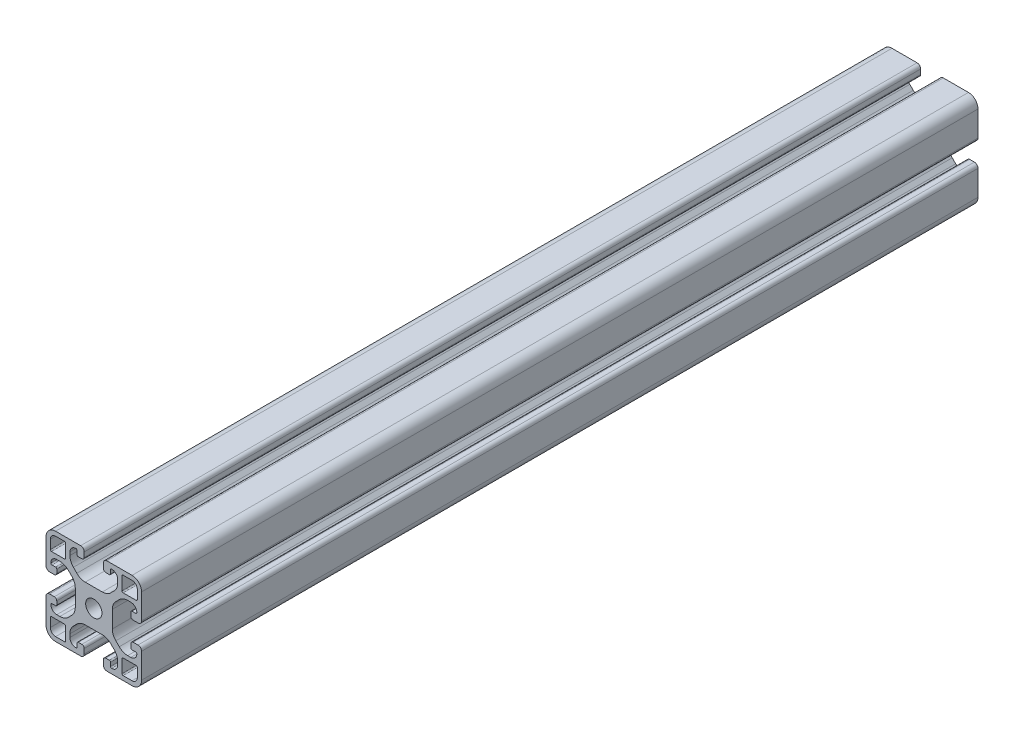
SolidWorks part; units mm, degrees
ref_plane "Front Plane" through (0, 0, 0) normal (0, 0, 1) x (1, 0, 0)
ref_plane "Top Plane" through (0, 0, 0) normal (0, 1, 0) x (1, 0, 0)
ref_plane "Right Plane" through (0, 0, 0) normal (1, 0, 0) x (0, 0, -1)
sketch "Sketch1" plane through (0, 0, 0) normal (0, 0, 1) x (1, 0, 0)
  line L0 (1.8, 4) -> (1.8, 7.7)
  line L1 (2.3, 8.2) -> (7.7, 8.2)
  line L2 (8.2, 7.7) -> (8.2, 2.3)
  line L3 (7.7, 1.8) -> (4, 1.8)
  line L4 (4, 38.2) -> (7.7, 38.2)
  line L5 (8.2, 37.7) -> (8.2, 32.3)
  line L6 (7.7, 31.8) -> (2.3, 31.8)
  line L7 (1.8, 32.3) -> (1.8, 36)
  line L8 (31.8, 32.3) -> (31.8, 37.7)
  line L9 (32.3, 38.2) -> (36, 38.2)
  line L10 (38.2, 36) -> (38.2, 32.3)
  line L11 (37.7, 31.8) -> (32.3, 31.8)
  line L12 (32.3, 8.2) -> (37.7, 8.2)
  line L13 (38.2, 7.7) -> (38.2, 4)
  line L14 (36, 1.8) -> (32.3, 1.8)
  line L15 (31.8, 2.3) -> (31.8, 7.7)
  line L16 (0, 36) -> (0, 25.5)
  line L17 (1.5, 24) -> (3.5, 24)
  line L18 (4.5, 25) -> (4.5, 26.5)
  line L19 (4, 27) -> (2.5, 27)
  line L20 (4.5, 30) -> (5.8076, 30)
  line L21 (9.3431, 28.5355) -> (10.7855, 27.0931)
  line L22 (12.25, 23.5576) -> (12.25, 16.4424)
  line L23 (10.7855, 12.9069) -> (9.3431, 11.4645)
  line L24 (5.8076, 10) -> (4.5, 10)
  line L25 (2.5, 13) -> (4, 13)
  line L26 (4.5, 13.5) -> (4.5, 15)
  line L27 (3.5, 16) -> (1.5, 16)
  line L28 (0, 14.5) -> (0, 4)
  line L29 (4, 0) -> (14.5, 0)
  line L30 (16, 1.5) -> (16, 3.5)
  line L31 (15, 4.5) -> (13.5, 4.5)
  line L32 (13, 4) -> (13, 2.5)
  line L33 (10, 4.5) -> (10, 5.8076)
  line L34 (11.4645, 9.3431) -> (12.9069, 10.7855)
  line L35 (16.4424, 12.25) -> (23.5576, 12.25)
  line L36 (27.0931, 10.7855) -> (28.5355, 9.3431)
  line L37 (30, 5.8076) -> (30, 4.5)
  line L38 (27, 2.5) -> (27, 4)
  line L39 (26.5, 4.5) -> (25, 4.5)
  line L40 (24, 3.5) -> (24, 1.5)
  line L41 (25.5, 0) -> (36, 0)
  line L42 (40, 4) -> (40, 14.5)
  line L43 (38.5, 16) -> (36.5, 16)
  line L44 (35.5, 15) -> (35.5, 13.5)
  line L45 (36, 13) -> (37.5, 13)
  line L46 (35.5, 10) -> (34.1924, 10)
  line L47 (30.6569, 11.4645) -> (29.2145, 12.9069)
  line L48 (27.75, 16.4424) -> (27.75, 23.5576)
  line L49 (29.2145, 27.0931) -> (30.6569, 28.5355)
  line L50 (34.1924, 30) -> (35.5, 30)
  line L51 (37.5, 27) -> (36, 27)
  line L52 (35.5, 26.5) -> (35.5, 25)
  line L53 (36.5, 24) -> (38.5, 24)
  line L54 (40, 25.5) -> (40, 36)
  line L55 (36, 40) -> (25.5, 40)
  line L56 (24, 38.5) -> (24, 36.5)
  line L57 (25, 35.5) -> (26.5, 35.5)
  line L58 (27, 36) -> (27, 37.5)
  line L59 (30, 35.5) -> (30, 34.1924)
  line L60 (28.5355, 30.6569) -> (27.0931, 29.2145)
  line L61 (23.5576, 27.75) -> (16.4424, 27.75)
  line L62 (12.9069, 29.2145) -> (11.4645, 30.6569)
  line L63 (10, 34.1924) -> (10, 35.5)
  line L64 (13, 37.5) -> (13, 36)
  line L65 (13.5, 35.5) -> (15, 35.5)
  line L66 (16, 36.5) -> (16, 38.5)
  line L67 (14.5, 40) -> (4, 40)
  arc A0 (1.8, 7.7) -> (2.3, 8.2) centre (2.3, 7.7) cw
  arc A1 (7.7, 8.2) -> (8.2, 7.7) centre (7.7, 7.7) cw
  arc A2 (8.2, 2.3) -> (7.7, 1.8) centre (7.7, 2.3) cw
  arc A3 (4, 1.8) -> (1.8, 4) centre (4, 4) cw
  arc A4 (1.8, 36) -> (4, 38.2) centre (4, 36) cw
  arc A5 (7.7, 38.2) -> (8.2, 37.7) centre (7.7, 37.7) cw
  arc A6 (8.2, 32.3) -> (7.7, 31.8) centre (7.7, 32.3) cw
  arc A7 (2.3, 31.8) -> (1.8, 32.3) centre (2.3, 32.3) cw
  circle A8 centre (20, 20) radius 3.4
  arc A9 (31.8, 37.7) -> (32.3, 38.2) centre (32.3, 37.7) cw
  arc A10 (36, 38.2) -> (38.2, 36) centre (36, 36) cw
  arc A11 (38.2, 32.3) -> (37.7, 31.8) centre (37.7, 32.3) cw
  arc A12 (32.3, 31.8) -> (31.8, 32.3) centre (32.3, 32.3) cw
  arc A13 (31.8, 7.7) -> (32.3, 8.2) centre (32.3, 7.7) cw
  arc A14 (37.7, 8.2) -> (38.2, 7.7) centre (37.7, 7.7) cw
  arc A15 (38.2, 4) -> (36, 1.8) centre (36, 4) cw
  arc A16 (32.3, 1.8) -> (31.8, 2.3) centre (32.3, 2.3) cw
  arc A17 (0, 25.5) -> (1.5, 24) centre (1.5, 25.5) ccw
  arc A18 (3.5, 24) -> (4.5, 25) centre (3.5, 25) ccw
  arc A19 (4.5, 26.5) -> (4, 27) centre (4, 26.5) ccw
  arc A20 (2.5, 27) -> (2, 27.5) centre (2.5, 27.5) cw
  arc A21 (2, 27.5) -> (4.5, 30) centre (4.5, 27.5) cw
  arc A22 (5.8076, 30) -> (9.3431, 28.5355) centre (5.8076, 25) cw
  arc A23 (10.7855, 27.0931) -> (12.25, 23.5576) centre (7.25, 23.5576) cw
  arc A24 (12.25, 16.4424) -> (10.7855, 12.9069) centre (7.25, 16.4424) cw
  arc A25 (9.3431, 11.4645) -> (5.8076, 10) centre (5.8076, 15) cw
  arc A26 (4.5, 10) -> (2, 12.5) centre (4.5, 12.5) cw
  arc A27 (2, 12.5) -> (2.5, 13) centre (2.5, 12.5) cw
  arc A28 (4, 13) -> (4.5, 13.5) centre (4, 13.5) ccw
  arc A29 (4.5, 15) -> (3.5, 16) centre (3.5, 15) ccw
  arc A30 (1.5, 16) -> (0, 14.5) centre (1.5, 14.5) ccw
  arc A31 (0, 4) -> (4, 0) centre (4, 4) ccw
  arc A32 (14.5, 0) -> (16, 1.5) centre (14.5, 1.5) ccw
  arc A33 (16, 3.5) -> (15, 4.5) centre (15, 3.5) ccw
  arc A34 (13.5, 4.5) -> (13, 4) centre (13.5, 4) ccw
  arc A35 (13, 2.5) -> (12.5, 2) centre (12.5, 2.5) cw
  arc A36 (12.5, 2) -> (10, 4.5) centre (12.5, 4.5) cw
  arc A37 (10, 5.8076) -> (11.4645, 9.3431) centre (15, 5.8076) cw
  arc A38 (12.9069, 10.7855) -> (16.4424, 12.25) centre (16.4424, 7.25) cw
  arc A39 (23.5576, 12.25) -> (27.0931, 10.7855) centre (23.5576, 7.25) cw
  arc A40 (28.5355, 9.3431) -> (30, 5.8076) centre (25, 5.8076) cw
  arc A41 (30, 4.5) -> (27.5, 2) centre (27.5, 4.5) cw
  arc A42 (27.5, 2) -> (27, 2.5) centre (27.5, 2.5) cw
  arc A43 (27, 4) -> (26.5, 4.5) centre (26.5, 4) ccw
  arc A44 (25, 4.5) -> (24, 3.5) centre (25, 3.5) ccw
  arc A45 (24, 1.5) -> (25.5, 0) centre (25.5, 1.5) ccw
  arc A46 (36, 0) -> (40, 4) centre (36, 4) ccw
  arc A47 (40, 14.5) -> (38.5, 16) centre (38.5, 14.5) ccw
  arc A48 (36.5, 16) -> (35.5, 15) centre (36.5, 15) ccw
  arc A49 (35.5, 13.5) -> (36, 13) centre (36, 13.5) ccw
  arc A50 (37.5, 13) -> (38, 12.5) centre (37.5, 12.5) cw
  arc A51 (38, 12.5) -> (35.5, 10) centre (35.5, 12.5) cw
  arc A52 (34.1924, 10) -> (30.6569, 11.4645) centre (34.1924, 15) cw
  arc A53 (29.2145, 12.9069) -> (27.75, 16.4424) centre (32.75, 16.4424) cw
  arc A54 (27.75, 23.5576) -> (29.2145, 27.0931) centre (32.75, 23.5576) cw
  arc A55 (30.6569, 28.5355) -> (34.1924, 30) centre (34.1924, 25) cw
  arc A56 (35.5, 30) -> (38, 27.5) centre (35.5, 27.5) cw
  arc A57 (38, 27.5) -> (37.5, 27) centre (37.5, 27.5) cw
  arc A58 (36, 27) -> (35.5, 26.5) centre (36, 26.5) ccw
  arc A59 (35.5, 25) -> (36.5, 24) centre (36.5, 25) ccw
  arc A60 (38.5, 24) -> (40, 25.5) centre (38.5, 25.5) ccw
  arc A61 (40, 36) -> (36, 40) centre (36, 36) ccw
  arc A62 (25.5, 40) -> (24, 38.5) centre (25.5, 38.5) ccw
  arc A63 (24, 36.5) -> (25, 35.5) centre (25, 36.5) ccw
  arc A64 (26.5, 35.5) -> (27, 36) centre (26.5, 36) ccw
  arc A65 (27, 37.5) -> (27.5, 38) centre (27.5, 37.5) cw
  arc A66 (27.5, 38) -> (30, 35.5) centre (27.5, 35.5) cw
  arc A67 (30, 34.1924) -> (28.5355, 30.6569) centre (25, 34.1924) cw
  arc A68 (27.0931, 29.2145) -> (23.5576, 27.75) centre (23.5576, 32.75) cw
  arc A69 (16.4424, 27.75) -> (12.9069, 29.2145) centre (16.4424, 32.75) cw
  arc A70 (11.4645, 30.6569) -> (10, 34.1924) centre (15, 34.1924) cw
  arc A71 (10, 35.5) -> (12.5, 38) centre (12.5, 35.5) cw
  arc A72 (12.5, 38) -> (13, 37.5) centre (12.5, 37.5) cw
  arc A73 (13, 36) -> (13.5, 35.5) centre (13.5, 36) ccw
  arc A74 (15, 35.5) -> (16, 36.5) centre (15, 36.5) ccw
  arc A75 (16, 38.5) -> (14.5, 40) centre (14.5, 38.5) ccw
  arc A76 (4, 40) -> (0, 36) centre (4, 36) ccw
  dimension "D1" = 20
  dimension "D2" = 20
  dimension "D3" = 6.8
  dimension "D4" = 15.5
  dimension "D5" = 15.5
extrude "Boss-Extrude1" add sketch "Sketch1" against normal blind 350
